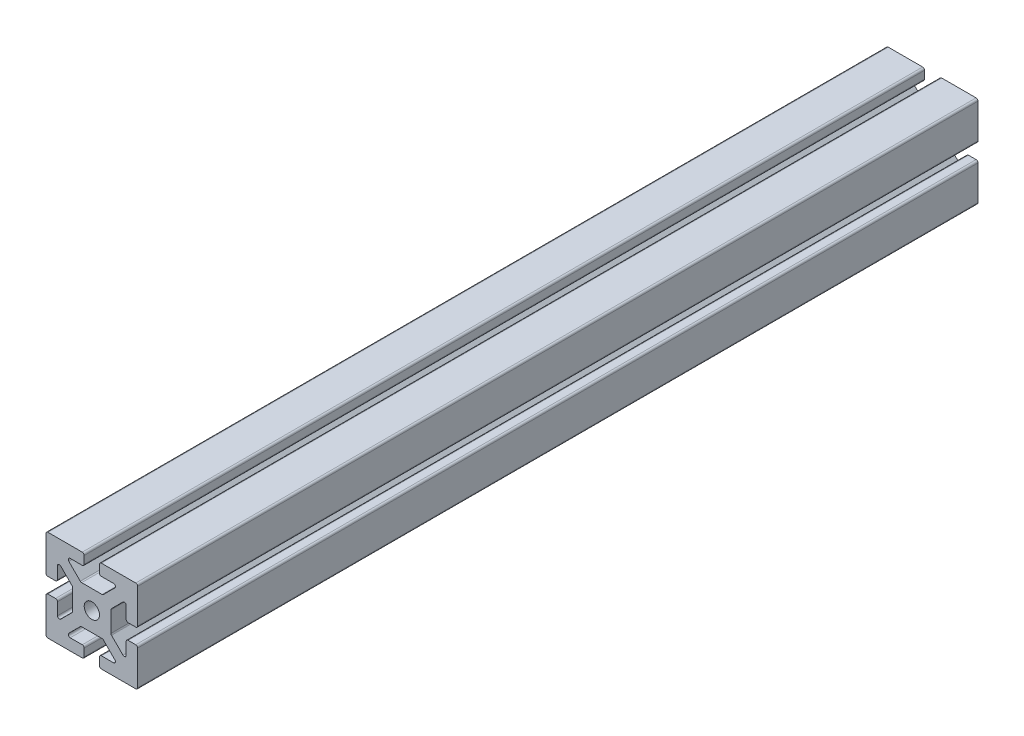
SolidWorks part; units mm, degrees
ref_plane "Front Plane" through (0, 0, 0) normal (0, 0, 1) x (1, 0, 0)
ref_plane "Top Plane" through (0, 0, 0) normal (0, 1, 0) x (1, 0, 0)
ref_plane "Right Plane" through (0, 0, 0) normal (1, 0, 0) x (0, 0, -1)
sketch "Sketch1" plane through (0, 0, 0) normal (0, 0, 1) x (1, 0, 0)
  line L0 (1002.2768, 0) -> (0, 0) construction
  line L1 (0, -1001.6534) -> (0, 1) construction
  line L2 (0, 0) -> (-6.9205, 6.9205) construction
  line L3 (-6, 1.25) -> (-6, 5.75)
  line L4 (-1.4393, -2.5) -> (1.3358, -2.5)
  line L5 (-2.5, -1.3358) -> (-2.5, 1.3358)
  line L6 (-1.3358, 2.5) -> (1.3358, 2.5)
  line L7 (2.5, -1.3358) -> (2.5, 1.3358)
  line L9 (-2.5, 2.5) -> (0, 0) construction
  line L10 (-0.998, -0.0626) -> (-1.0607, 0)
  line L11 (0, 0) -> (-6.3689, 6.3689) construction
  line L12 (-1.25, 4.5) -> (-2.8358, 4.5)
  line L13 (-4.75, 1) -> (-5.75, 1)
  line L14 (-4.5, 3.1592) -> (-4.5, 3.4393)
  line L15 (-0.5303, -0.5303) -> (-6.8992, 5.8386) construction
  line L16 (-1, 4.75) -> (-1, 5.75)
  line L17 (-1.25, 6) -> (-5.75, 6)
  line L18 (-4.5, 1.25) -> (-4.5, 2.8358)
  line L19 (1.25, 6) -> (5.75, 6)
  line L20 (6, 1.25) -> (6, 5.75)
  line L21 (4.75, 1) -> (5.75, 1)
  line L22 (-1.5126, 2.5732) -> (-3.0126, 4.0732)
  line L23 (0, 2.5) -> (0, 1003.3466) construction
  line L24 (4.5, 1.25) -> (4.5, 2.8358)
  line L25 (2.5732, 1.5126) -> (4.0732, 3.0126)
  line L26 (1.5126, 2.5732) -> (3.0126, 4.0732)
  line L27 (1.25, 4.5) -> (2.8358, 4.5)
  line L28 (0.998, -0.0626) -> (1.0607, 0)
  line L29 (-1, 0) -> (-1002.2768, 0) construction
  line L30 (1, 4.75) -> (1, 5.75)
  line L31 (-2.5732, 1.5126) -> (-4.0732, 3.0126)
  line L32 (1, -4.75) -> (1, -5.75)
  line L33 (4.75, -1) -> (5.75, -1)
  line L34 (1.25, -4.5) -> (2.8358, -4.5)
  line L35 (1.5126, -2.5732) -> (3.0126, -4.0732)
  line L36 (2.5732, -1.5126) -> (4.0732, -3.0126)
  line L37 (4.5, -1.25) -> (4.5, -2.8358)
  line L38 (6, -1.25) -> (6, -5.75)
  line L39 (1.25, -6) -> (5.75, -6)
  line L40 (-1.4393, -2.5) -> (-3.0126, -4.0732)
  line L41 (-1, -4.75) -> (-1, -5.75)
  line L42 (-1.25, -4.5) -> (-2.8358, -4.5)
  line L44 (-2.5732, -1.5126) -> (-4.0732, -3.0126)
  line L45 (-4.5, -1.25) -> (-4.5, -2.8358)
  line L46 (-1.25, -6) -> (-5.75, -6)
  line L47 (-4.5, -3.1592) -> (-4.5, -3.4393)
  line L48 (-4.75, -1) -> (-5.75, -1)
  line L49 (-6, -1.25) -> (-6, -5.75)
  circle A0 centre (0, 0) radius 1
  arc A1 (-6, 1.25) -> (-5.75, 1) centre (-5.75, 1.25) ccw
  arc A2 (-4.5, 1.25) -> (-4.75, 1) centre (-4.75, 1.25) cw
  arc A3 (-4.5, 2.8358) -> (-4.0732, 3.0126) centre (-4.25, 2.8358) cw
  arc A4 (-3.0126, 4.0732) -> (-2.8358, 4.5) centre (-2.8358, 4.25) cw
  arc A5 (-1, 4.75) -> (-1.25, 4.5) centre (-1.25, 4.75) cw
  arc A6 (-1, 5.75) -> (-1.25, 6) centre (-1.25, 5.75) ccw
  arc A7 (-6, 5.75) -> (-5.75, 6) centre (-5.75, 5.75) cw
  arc A8 (6, 5.75) -> (5.75, 6) centre (5.75, 5.75) ccw
  arc A9 (6, 1.25) -> (5.75, 1) centre (5.75, 1.25) cw
  arc A10 (4.5, 1.25) -> (4.75, 1) centre (4.75, 1.25) ccw
  arc A11 (4.5, 2.8358) -> (4.0732, 3.0126) centre (4.25, 2.8358) ccw
  arc A12 (3.0126, 4.0732) -> (2.8358, 4.5) centre (2.8358, 4.25) ccw
  arc A13 (1, 4.75) -> (1.25, 4.5) centre (1.25, 4.75) ccw
  arc A14 (1, 5.75) -> (1.25, 6) centre (1.25, 5.75) cw
  arc A15 (1, -5.75) -> (1.25, -6) centre (1.25, -5.75) ccw
  arc A16 (1, -4.75) -> (1.25, -4.5) centre (1.25, -4.75) cw
  arc A17 (6, -1.25) -> (5.75, -1) centre (5.75, -1.25) ccw
  arc A18 (4.5, -1.25) -> (4.75, -1) centre (4.75, -1.25) cw
  arc A19 (3.0126, -4.0732) -> (2.8358, -4.5) centre (2.8358, -4.25) cw
  arc A20 (4.5, -2.8358) -> (4.0732, -3.0126) centre (4.25, -2.8358) cw
  arc A21 (6, -5.75) -> (5.75, -6) centre (5.75, -5.75) cw
  arc A22 (-3.0126, -4.0732) -> (-2.8358, -4.5) centre (-2.8358, -4.25) ccw
  arc A23 (-1, -5.75) -> (-1.25, -6) centre (-1.25, -5.75) cw
  arc A24 (-1, -4.75) -> (-1.25, -4.5) centre (-1.25, -4.75) ccw
  arc A25 (-6, -5.75) -> (-5.75, -6) centre (-5.75, -5.75) ccw
  arc A26 (-4.5, -2.8358) -> (-4.0732, -3.0126) centre (-4.25, -2.8358) ccw
  arc A27 (-4.5, -1.25) -> (-4.75, -1) centre (-4.75, -1.25) ccw
  arc A28 (-6, -1.25) -> (-5.75, -1) centre (-5.75, -1.25) cw
  arc A29 (1.5126, -2.5732) -> (1.3358, -2.5) centre (1.3358, -2.75) ccw
  arc A30 (2.5732, -1.5126) -> (2.5, -1.3358) centre (2.75, -1.3358) cw
  arc A31 (2.5, 1.3358) -> (2.5732, 1.5126) centre (2.75, 1.3358) cw
  arc A32 (1.3358, 2.5) -> (1.5126, 2.5732) centre (1.3358, 2.75) ccw
  arc A33 (-1.3358, 2.5) -> (-1.5126, 2.5732) centre (-1.3358, 2.75) cw
  arc A34 (-2.5, 1.3358) -> (-2.5732, 1.5126) centre (-2.75, 1.3358) ccw
  arc A35 (-2.5732, -1.5126) -> (-2.5, -1.3358) centre (-2.75, -1.3358) ccw
  point P6 (0, 0)
  point P9 (0, 0)
  point P13 (1.4393, -2.5)
  point P45 (-6, 1)
  point P48 (-4.5, 1)
  point P54 (-3.4393, 4.5)
  point P57 (-1, 4.5)
  point P60 (-1, 6)
  point P63 (-6, 6)
  point P65 (4.5, 1)
  point P79 (1, 5.25)
  point P110 (-1, -6)
  point P130 (-6, -6)
  point P131 (-4.5, -1)
  point P132 (-6, -1)
  point P134 (2.5, -1.4393)
  point P137 (2.5, 1.4393)
  point P140 (1.4393, 2.5)
  point P143 (-1.4393, 2.5)
  point P146 (-2.5, 1.4393)
  point P149 (-2.5, -1.4393)
  dimension "D1" = 2
  dimension "D8" = 0.25
  dimension "D9" = 0.25
  dimension "D2" = 45
  dimension "D3" = 2.5
  dimension "D4" = 2
  dimension "D6" = 1.5
  dimension "D7" = 2
  dimension "D5" = 0.75
extrude "Boss-Extrude1" add sketch "Sketch1" against normal blind 110
